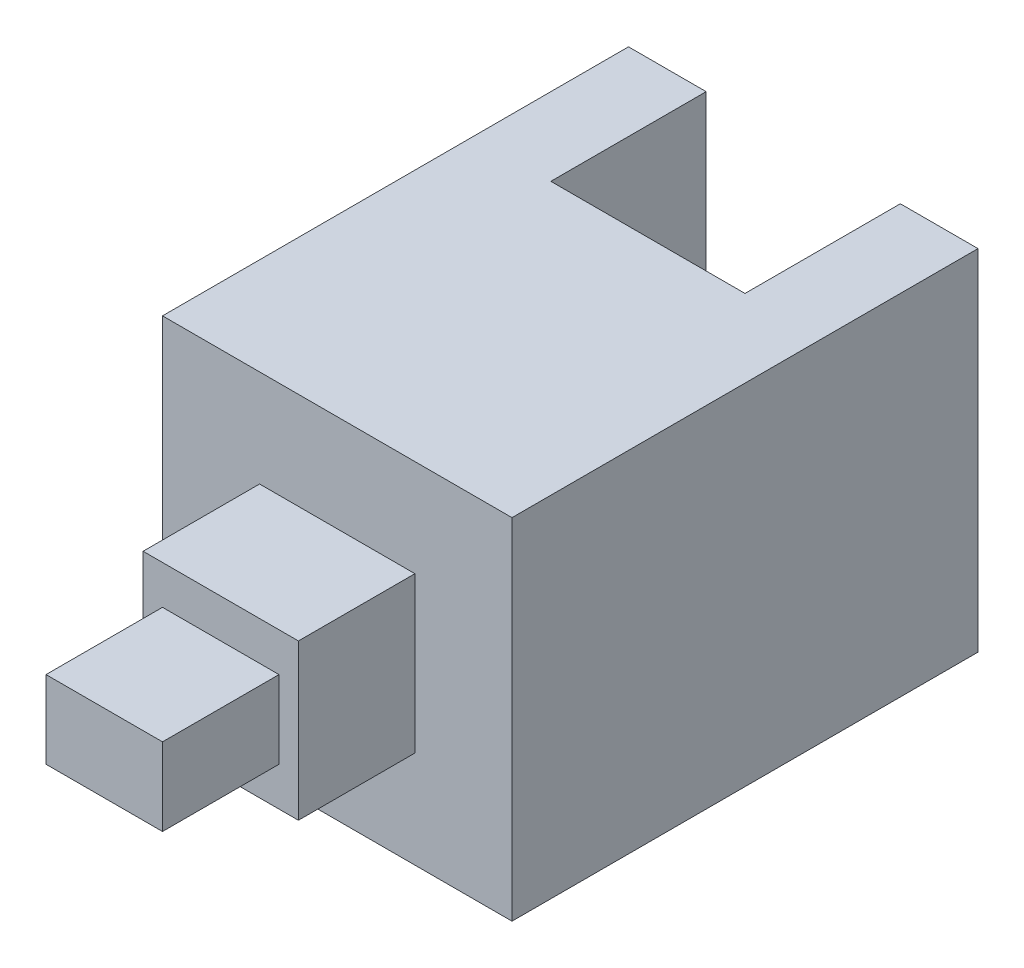
SolidWorks part; units mm, degrees
ref_plane "Front Plane" through (0, 0, 0) normal (0, 0, 1) x (1, 0, 0)
ref_plane "Top Plane" through (0, 0, 0) normal (0, 1, 0) x (1, 0, 0)
ref_plane "Right Plane" through (0, 0, 0) normal (1, 0, 0) x (0, 0, -1)
sketch "Sketch1" plane through (0, 0, 0) normal (0, 0, 1) x (1, 0, 0)
  line L1 (-4.5, 4.5) -> (4.5, 4.5)
  line L2 (-4.5, 4.5) -> (-4.5, -4.5)
  line L3 (-4.5, -4.5) -> (4.5, -4.5)
  line L4 (4.5, 4.5) -> (4.5, -4.5)
  line L5 (-4.5, 4.5) -> (4.5, -4.5) construction
  line L6 (-4.5, -4.5) -> (4.5, 4.5) construction
  point P0 (0, 0)
  dimension "D1" = 9
extrude "MAIN BODY" add sketch "Sketch1" along normal blind 8
sketch "Sketch2" plane through (0, 0, 8) normal (0, 0, 1) x (1, 0, 0)
  line L5 (-2, 2) -> (2, 2)
  line L6 (-2, 2) -> (-2, -2)
  line L7 (-2, -2) -> (2, -2)
  line L8 (2, 2) -> (2, -2)
  line L9 (-2, 2) -> (2, -2) construction
  line L10 (-2, -2) -> (2, 2) construction
  point P0 (0, 0)
  dimension "D1" = 4
extrude "Boss-Extrude2" add sketch "Sketch2" along normal blind 3
sketch "Sketch3" plane through (0, 0, 11) normal (0, 0, 1) x (1, 0, 0)
  line L1 (-1.5, 1) -> (1.5, 1)
  line L2 (-1.5, 1) -> (-1.5, -1)
  line L3 (-1.5, -1) -> (1.5, -1)
  line L4 (1.5, 1) -> (1.5, -1)
  point P4 (-1.5, 0)
  point P6 (0, 1)
  dimension "D1" = 3
  dimension "D2" = 2
extrude "Boss-Extrude3" add sketch "Sketch3" along normal blind 3
sketch "Sketch4" plane through (0, 0, 0) normal (0, 0, -1) x (-1, 0, 0)
  line L0 (-4.5, -4.5) -> (-4.5, 4.5) construction
  line L1 (-4.5, 4.5) -> (-2.5, 4.5)
  line L2 (-4.5, 4.5) -> (-4.5, -4.5)
  line L3 (-4.5, -4.5) -> (-2.5, -4.5)
  line L4 (-2.5, 4.5) -> (-2.5, -4.5)
  line L5 (-4.5, 4.5) -> (4.5, 4.5) construction
  line L6 (4.5, -4.5) -> (-4.5, -4.5) construction
  line L8 (4.5, 4.5) -> (2.5, 4.5)
  line L9 (4.5, 4.5) -> (4.5, -4.5)
  line L10 (4.5, -4.5) -> (2.5, -4.5)
  line L11 (2.5, 4.5) -> (2.5, -4.5)
  dimension "D1" = 2
extrude "PINS" add sketch "Sketch4" along normal blind 4
